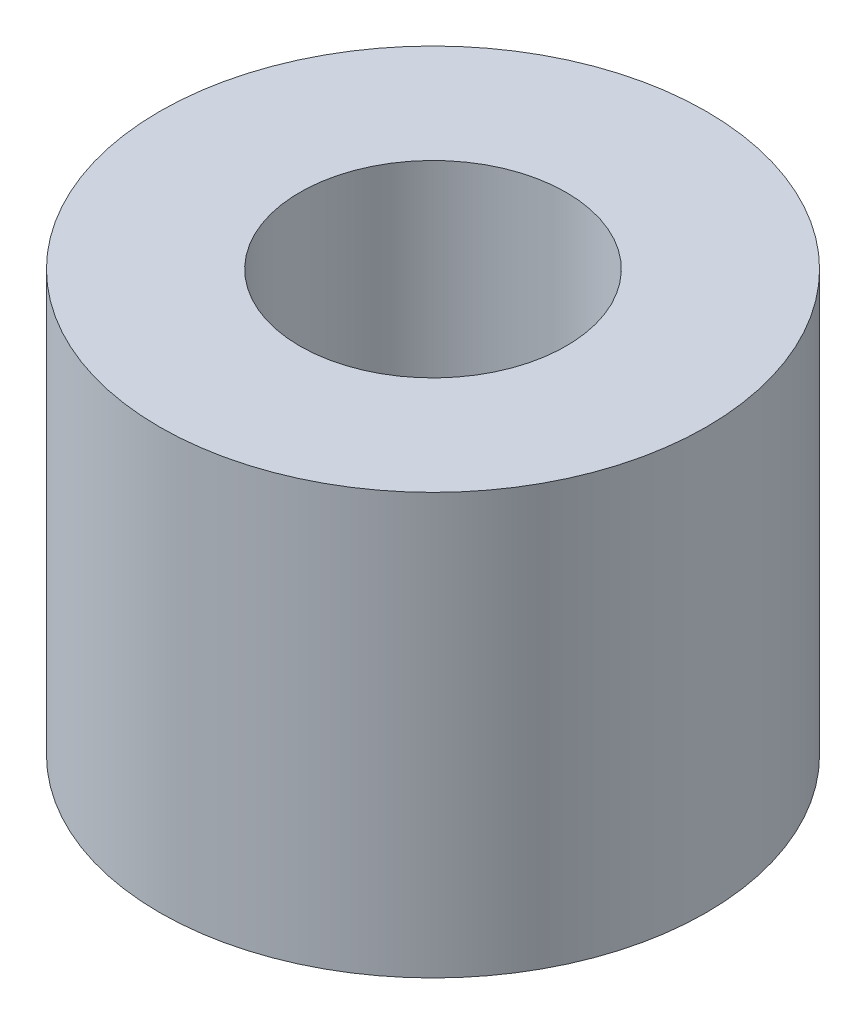
SolidWorks part; units mm, degrees
ref_plane "Front Plane" through (0, 0, 0) normal (0, 0, 1) x (1, 0, 0)
ref_plane "Top Plane" through (0, 0, 0) normal (0, 1, 0) x (1, 0, 0)
ref_plane "Right Plane" through (0, 0, 0) normal (1, 0, 0) x (0, 0, -1)
sketch "Sketch1" plane through (0, 0, 0) normal (0, 1, 0) x (1, 0, 0)
  circle A0 centre (0, 0) radius 0.95
  circle A1 centre (0, 0) radius 1.95
  dimension "D1" = 1.9
  dimension "D2" = 1
extrude "Boss-Extrude1" add sketch "Sketch1" along normal blind 3
